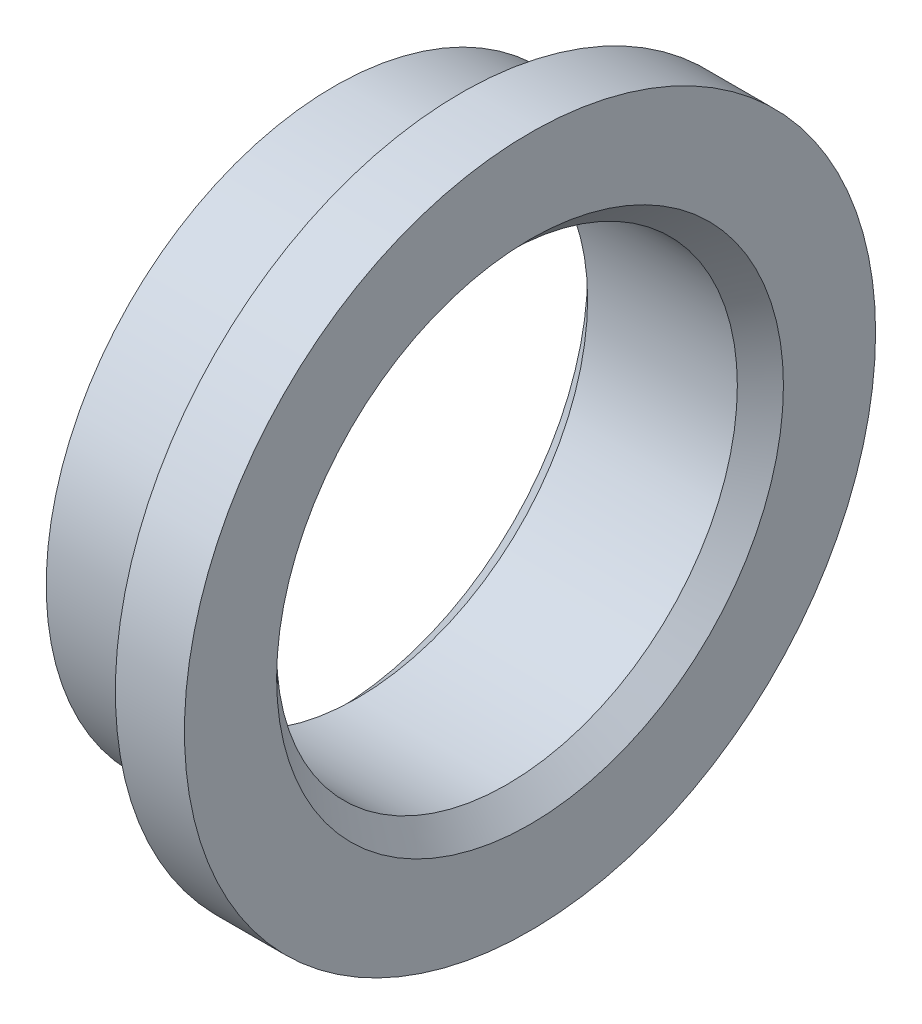
SolidWorks part; units mm, degrees
ref_plane "前视基准面" through (0, 0, 0) normal (0, 0, 1) x (1, 0, 0)
ref_plane "上视基准面" through (0, 0, 0) normal (0, 1, 0) x (1, 0, 0)
ref_plane "右视基准面" through (0, 0, 0) normal (1, 0, 0) x (0, 0, -1)
other "Configuration Table"
sketch "草图1" plane through (0, 0, 0) normal (0, 0, 1) x (1, 0, 0)
  line L0 (0, 0) -> (-7.3105, 0) construction
  line L1 (0, 10) -> (8.5, 10)
  line L2 (8.5, 10) -> (8.5, 15)
  line L3 (8.5, 15) -> (5.5, 15)
  line L4 (5.5, 15) -> (5.5, 12.5)
  line L5 (5.5, 12.5) -> (0, 12.5)
  line L6 (0, 12.5) -> (0, 10)
  dimension "D1" = 10
  dimension "D2" = 30
  dimension "D3" = 3
  dimension "D4" = 25
  dimension "D5" = 8.5
revolve "旋转1" add sketch "草图1" angle 360 about L0
chamfer "倒角1" distance 1 angle 45 2 edges at (0, 0, -10) (8.5, 0, -10)
